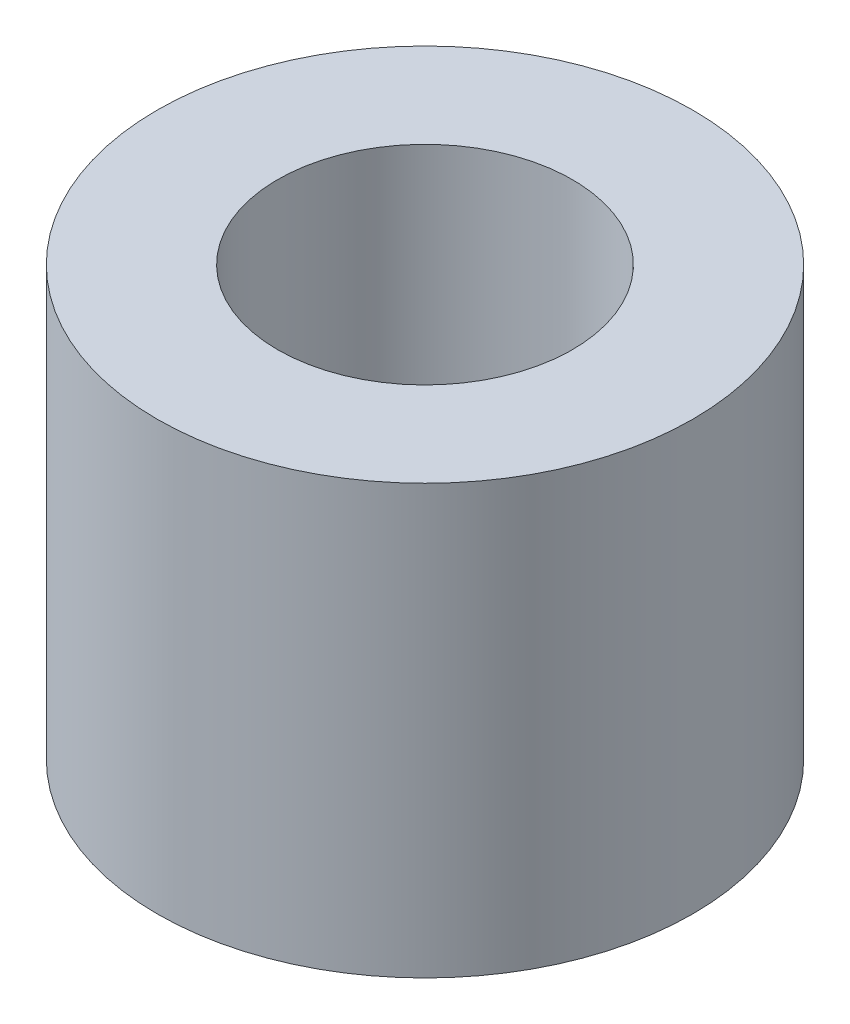
SolidWorks part; units mm, degrees
material "Alloy Steel"
ref_plane "Front Plane" through (0, 0, 0) normal (0, 0, 1) x (1, 0, 0)
ref_plane "Top Plane" through (0, 0, 0) normal (0, 1, 0) x (1, 0, 0)
ref_plane "Right Plane" through (0, 0, 0) normal (1, 0, 0) x (0, 0, -1)
sketch "Sketch1" plane through (0, 0, 0) normal (0, 1, 0) x (1, 0, 0)
  circle A0 centre (0, 0) radius 7.9375
  circle A1 centre (0, 0) radius 4.3688
  dimension "D1" = 15.875
  dimension "D2" = 8.7376
extrude "Boss-Extrude1" add sketch "Sketch1" along normal blind 12.7
